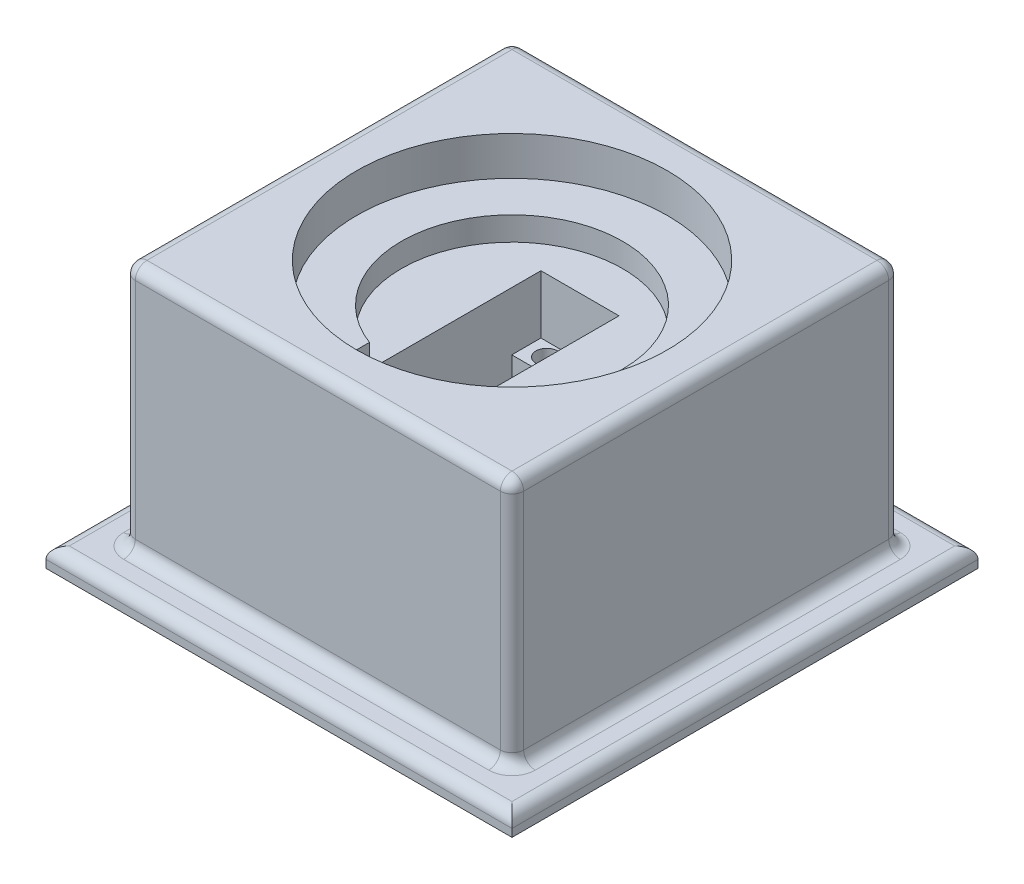
SolidWorks part; units mm, degrees
ref_plane "Front Plane" through (0, 0, 0) normal (0, 0, 1) x (1, 0, 0)
ref_plane "Top Plane" through (0, 0, 0) normal (0, 1, 0) x (1, 0, 0)
ref_plane "Right Plane" through (0, 0, 0) normal (1, 0, 0) x (0, 0, -1)
sketch "Sketch1" plane through (0, 0, 0) normal (0, 1, 0) x (1, 0, 0)
  line L1 (-50, -50) -> (50, -50)
  line L2 (-50, -50) -> (-50, 50)
  line L3 (-50, 50) -> (50, 50)
  line L4 (50, -50) -> (50, 50)
  line L5 (-50, -50) -> (50, 50) construction
  line L6 (-50, 50) -> (50, -50) construction
  point P0 (0, 0)
  dimension "D1" = 100
extrude "Boss-Extrude1" add sketch "Sketch1" along normal blind 68.7 contours L4 L3 L2 L1
sketch "Sketch2" plane through (0, 68.7, 0) normal (0, 1, 0) x (1, 0, 0)
  circle A0 centre (0, 0) radius 40
  dimension "D1" = 80
extrude "Cut-Extrude1" cut sketch "Sketch2" against normal blind 10
sketch "Sketch3" plane through (0, 58.7, 0) normal (0, 1, 0) x (1, 0, 0)
  circle A0 centre (0, 0) radius 28.5
  dimension "D1" = 57
extrude "Cut-Extrude2" cut sketch "Sketch3" against normal blind 6.1
sketch "Sketch4" plane through (0, 52.6, 0) normal (0, 1, 0) x (1, 0, 0)
  line L1 (-10.055, 17.5) -> (10.055, 17.5)
  line L2 (-10.055, 17.5) -> (-10.055, -37.51)
  line L3 (-10.055, -37.51) -> (10.055, -37.51)
  line L4 (10.055, 17.5) -> (10.055, -37.51)
  point P4 (0, 17.5)
  dimension "D1" = 20.11
  dimension "D2" = 55.01
  dimension "D3" = 17.5
extrude "Cut-Extrude3" cut sketch "Sketch4" against normal blind 15.01 and the other way through all
sketch "Sketch5" plane through (0, 37.59, 0) normal (0, 1, 0) x (1, 0, 0)
  line L0 (10.055, 17.5) -> (10.055, -26.6673) construction
  line L1 (-10.055, 10) -> (10.055, 10)
  line L2 (-10.055, 10) -> (-10.055, -30.11)
  line L3 (-10.055, -30.11) -> (10.055, -30.11)
  line L4 (10.055, 10) -> (10.055, -30.11)
  dimension "D1" = 20.11
  dimension "D2" = 40.11
  dimension "D3" = 10
extrude "Cut-Extrude4" cut sketch "Sketch5" against normal blind 27.51
sketch "Sketch6" plane through (0, 0, -50) normal (0, 0, -1) x (-1, 0, 0)
  line L0 (-3.5, 13.08) -> (3.5, 13.08)
  line L1 (3.5, 13.08) -> (3.5, 17.58)
  line L2 (-3.5, 13.08) -> (-3.5, 17.58)
  line L8 (50, 0) -> (-50, 0) construction
  arc A0 (3.5, 17.58) -> (-3.5, 17.58) centre (0, 17.58) ccw
  point P13 (0, 13.08)
  dimension "D1" = 13.08
  dimension "D2" = 7
  dimension "D3" = 4.5
extrude "Cut-Extrude5" cut sketch "Sketch6" against normal up to next contours L1 A0 L2 L0
sketch "Sketch7" plane through (0, 37.59, 0) normal (0, 1, 0) x (1, 0, 0)
  line L0 (-10.055, -37.51) -> (10.055, -37.51) construction
  line L1 (10.055, -26.6673) -> (10.055, -37.51) construction
  line L2 (-10.055, -30.11) -> (-10.055, -37.51) construction
  line L4 (10.055, 17.5) -> (10.055, -26.6673) construction
  line L5 (-10.055, 17.5) -> (-10.055, 10) construction
  line L6 (-10.055, 17.5) -> (10.055, 17.5) construction
  circle A0 centre (5.055, -34.01) radius 2.775
  circle A1 centre (-5.055, -34.01) radius 2.775
  circle A2 centre (-5.055, 14) radius 2.775
  circle A3 centre (5.055, 14) radius 2.775
  dimension "D1" = 5
  dimension "D2" = 5.55
  dimension "D6" = 5
  dimension "D7" = 3.5
  dimension "D3" = 3.5
  dimension "D4" = 5
  dimension "D5" = 5
extrude "Cut-Extrude6" cut sketch "Sketch7" against normal blind 3.2
sketch "Sketch8" plane through (0, 0, -10) normal (0, 0, 1) x (1, 0, 0)
  line L0 (-3.5, 13.08) -> (3.5, 13.08)
  line L1 (3.5, 13.08) -> (3.5, 31.08)
  line L2 (-3.5, 13.08) -> (-3.5, 31.08)
  arc A0 (3.5, 31.08) -> (-3.5, 31.08) centre (0, 31.08) ccw
  dimension "D1" = 18
extrude "Cut-Extrude7" cut sketch "Sketch8" against normal blind 5
sketch "Sketch9" plane through (0, 0, 0) normal (0, -1, 0) x (1, 0, 0)
  line L8 (60, 60) -> (-60, 60)
  line L9 (-60, 60) -> (-60, -60)
  line L10 (-60, -60) -> (60, -60)
  line L11 (60, -60) -> (60, 60)
  line L12 (60, 60) -> (-60, 60)
  line L13 (-60, 60) -> (-60, -60)
  line L14 (-60, -60) -> (60, -60)
  line L15 (60, -60) -> (60, 60)
  dimension "D1" = 10
extrude "Boss-Extrude2" add sketch "Sketch9" against normal blind 5
fillet "Fillet2" radius 3 16 edges at (0, 5, -50) (0, 5, 60) (-60, 5, 0) (0, 5, -60) (60, 5, 0) (-50, 68.7, 0) (-50, 5, 0) (-50, 36.85, -50) (-50, 36.85, 50) (0, 68.7, 50) (0, 5, 50) (50, 36.85, 50) (50, 68.7, 0) (50, 36.85, -50) (50, 5, 0) (0, 68.7, -50)
